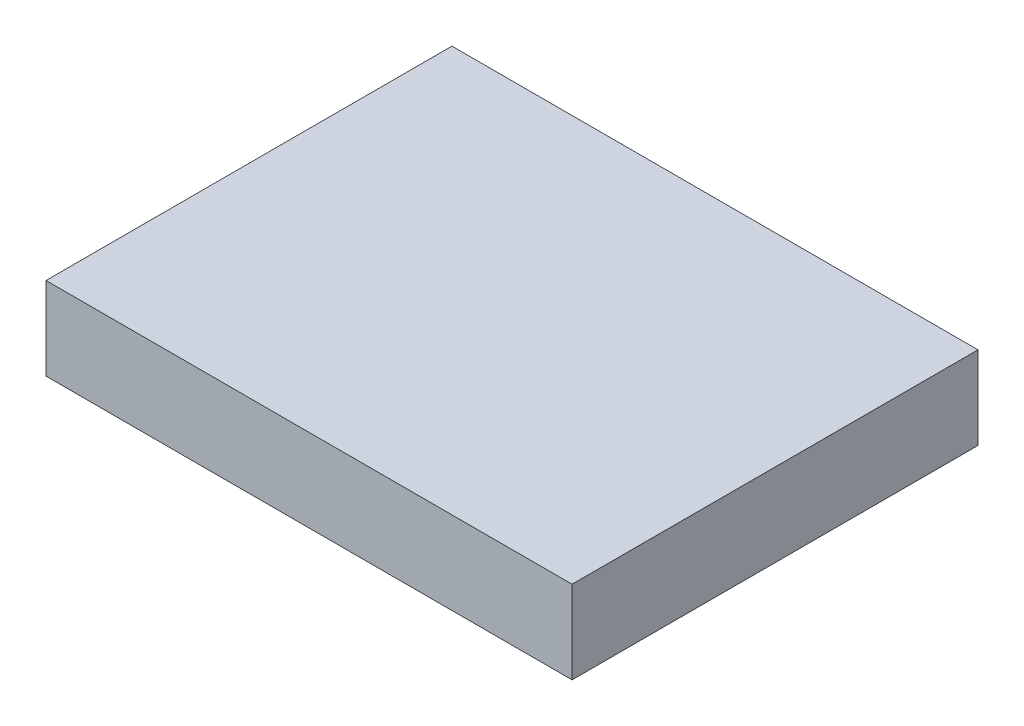
SolidWorks part; units mm, degrees
ref_plane "前视基准面" through (0, 0, 0) normal (0, 0, 1) x (1, 0, 0)
ref_plane "上视基准面" through (0, 0, 0) normal (0, 1, 0) x (1, 0, 0)
ref_plane "右视基准面" through (0, 0, 0) normal (1, 0, 0) x (0, 0, -1)
sketch "草图1" plane through (0, 0, 0) normal (0, 1, 0) x (1, 0, 0)
  line L0 (0, 63.7332) -> (0, -75.9309) construction
  line L1 (-63.5, 49) -> (63.5, 49)
  line L2 (-63.5, 49) -> (-63.5, -49)
  line L3 (-63.5, -49) -> (63.5, -49)
  line L4 (63.5, 49) -> (63.5, -49)
  line L5 (-96.0572, 0) -> (117.7082, 0) construction
  dimension "D1" = 127
  dimension "D2" = 98
extrude "拉伸1" add sketch "草图1" along normal blind 20
